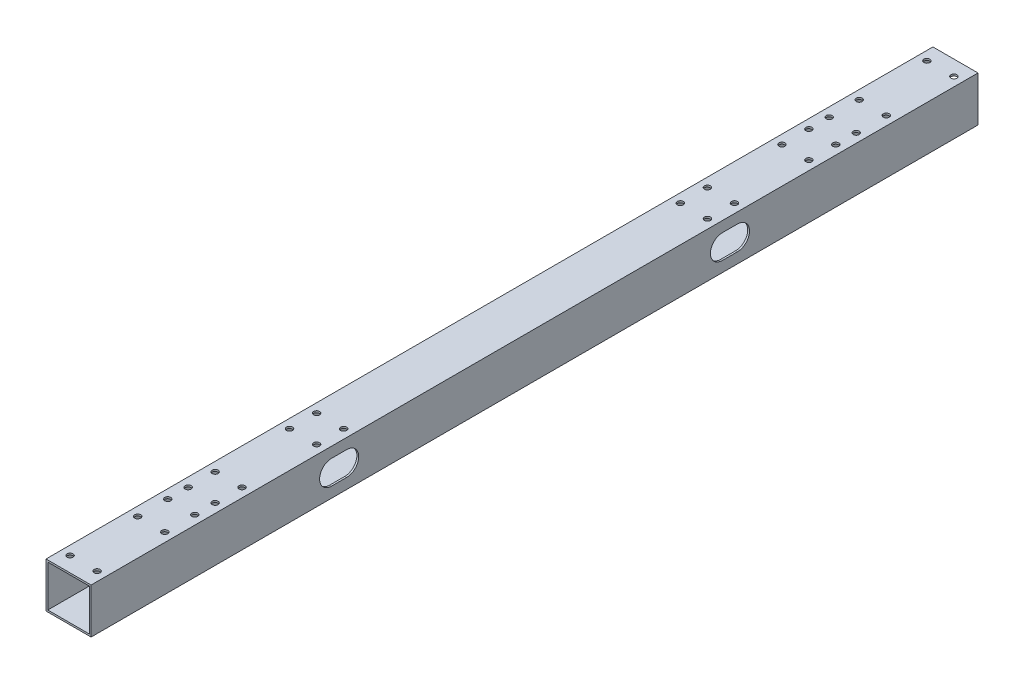
SolidWorks part; units mm, degrees
material "6063-T5"
ref_plane "前视基准面" through (0, 0, 0) normal (0, 0, 1) x (1, 0, 0)
ref_plane "上视基准面" through (0, 0, 0) normal (0, 1, 0) x (1, 0, 0)
ref_plane "右视基准面" through (0, 0, 0) normal (1, 0, 0) x (0, 0, -1)
sketch "草图1" plane through (0, 0, 0) normal (0, 0, 1) x (1, 0, 0)
  line L0 (-13.8, -13.8) -> (-13.8, 13.8)
  line L1 (-15, -15) -> (15, -15)
  line L2 (-15, -15) -> (-15, 15)
  line L3 (-15, 15) -> (15, 15)
  line L4 (15, -15) -> (15, 15)
  line L5 (0, 15) -> (0, -15) construction
  line L6 (-15, 0) -> (15, 0) construction
  line L7 (-13.8, 13.8) -> (13.8, 13.8)
  line L8 (13.8, -13.8) -> (13.8, 13.8)
  line L9 (-13.8, -13.8) -> (13.8, -13.8)
  point P0 (0, 0)
  dimension "D1" = 30
  dimension "D2" = 30
  dimension "D3" = 1.2
extrude "凸台-拉伸1" add sketch "草图1" along normal mid plane 590
sketch "草图2" plane through (0, 15, 0) normal (0, 1, 0) x (1, 0, 0)
  line L0 (0, 0) -> (15, 0) construction
  line L1 (15, -295) -> (15, 295) construction
  circle A0 centre (-9, 220) radius 2 construction
  circle A1 centre (9, 220) radius 2 construction
  circle A2 centre (-9, 240) radius 2 construction
  circle A3 centre (9, 240) radius 2 construction
  circle A4 centre (-9, 220) radius 2
  circle A5 centre (9, 220) radius 2
  circle A6 centre (-9, 240) radius 2
  circle A7 centre (9, 240) radius 2
  circle A8 centre (9, -240) radius 2
  circle A9 centre (-9, -240) radius 2
  circle A10 centre (9, -220) radius 2
  circle A11 centre (-9, -220) radius 2
extrude "切除-拉伸1" cut sketch "草图2" against normal blind 10
sketch "草图3" plane through (0, -13.8, 0) normal (0, 1, 0) x (1, 0, 0)
  line L0 (0, 0) -> (15, 0) construction
  line L1 (15, -295) -> (15, 295) construction
  circle A0 centre (-9, 240) radius 4
  circle A1 centre (9, 240) radius 4
  circle A2 centre (-9, 220) radius 4
  circle A3 centre (9, 220) radius 4
  circle A4 centre (9, -220) radius 4
  circle A5 centre (-9, -220) radius 4
  circle A6 centre (9, -240) radius 4
  circle A7 centre (-9, -240) radius 4
  dimension "D1" = 8
extrude "切除-拉伸2" cut sketch "草图3" against normal blind 10
sketch "草图4" plane through (15, 0, 0) normal (1, 0, 0) x (0, 0, -1)
  line L0 (-115, 15) -> (-145, 15) construction
  line L1 (-115, 15) -> (-145, 15) construction
  line L2 (-130, 15) -> (-130, -15) construction
  line L3 (-295, -15) -> (295, -15) construction
  line L4 (-135, 0) -> (-125, 0) construction
  line L5 (-135, 8) -> (-125, 8)
  line L6 (-135, -8) -> (-125, -8)
  arc A0 (-135, 8) -> (-135, -8) centre (-135, 0) ccw
  arc A1 (-125, -8) -> (-125, 8) centre (-125, 0) ccw
  point P8 (-130, 0)
  dimension "D2" = 8
  dimension "D1" = 10
extrude "切除-拉伸3" cut sketch "草图4" against normal blind 111
mirror "镜向1" about plane through (0, 0, 0) normal (0, 0, 1) of "切除-拉伸3"
sketch "草图5" plane through (0, 15, 0) normal (0, 1, 0) x (1, 0, 0)
  line L1 (-9, -139) -> (9, -139) construction
  line L2 (-9, -139) -> (-9, -121) construction
  line L3 (-9, -121) -> (9, -121) construction
  line L4 (9, -139) -> (9, -121) construction
  line L5 (0, -121) -> (0, -139) construction
  line L6 (-9, -130) -> (9, -130) construction
  circle A0 centre (-9, -139) radius 2 construction
  circle A1 centre (-9, -121) radius 2 construction
  circle A2 centre (9, -121) radius 2 construction
  circle A3 centre (-9, -139) radius 2
  circle A4 centre (-9, -121) radius 2
  circle A5 centre (9, -121) radius 2
  circle A6 centre (9, -139) radius 2
  point P9 (0, -130)
extrude "切除-拉伸4" cut sketch "草图5" against normal blind 10
mirror "镜向2" about plane through (0, 0, 0) normal (0, 0, 1) of "切除-拉伸4"
sketch "草图6" plane through (0, 15, 0) normal (0, 1, 0) x (1, 0, 0)
  line L0 (-9, -285) -> (9, -285) construction
  line L1 (15, -295) -> (-15, -295) construction
  line L2 (0, 0) -> (0, -285) construction
  circle A0 centre (-9, -285) radius 2
  circle A1 centre (9, -285) radius 2
  point P3 (0, -285)
  dimension "D3" = 4
  dimension "D1" = 10
  dimension "D2" = 18
extrude "切除-拉伸5" cut sketch "草图6" against normal blind 10
mirror "镜向3" about plane through (0, 0, 0) normal (0, 0, 1) of "切除-拉伸5"
sketch "草图7" plane through (0, -15, 0) normal (0, -1, 0) x (1, 0, 0)
  circle A0 centre (0, 98.7384) radius 1.5 construction
  circle A1 centre (0, 38.7384) radius 1.5 construction
  circle A2 centre (0, -38.7384) radius 1.5 construction
  circle A3 centre (0, -98.7384) radius 1.5 construction
  circle A4 centre (0, 98.7384) radius 1.5
  circle A5 centre (0, 38.7384) radius 1.5
  circle A6 centre (0, -38.7384) radius 1.5
  circle A7 centre (0, -98.7384) radius 1.5
extrude "切除-拉伸6" cut sketch "草图7" against normal blind 10
sketch "草图8" plane through (0, 13.8, 0) normal (0, -1, 0) x (1, 0, 0)
  circle A0 centre (-8.95, 188.55) radius 1.65 construction
  circle A1 centre (8.95, 188.55) radius 1.65 construction
  circle A2 centre (8.95, 206.45) radius 1.65 construction
  circle A3 centre (-8.95, 206.45) radius 1.65 construction
  circle A4 centre (-8.95, 188.55) radius 1.65 construction
  circle A5 centre (8.95, 188.55) radius 1.65 construction
  circle A6 centre (8.95, 206.45) radius 1.65 construction
  circle A7 centre (-8.95, 206.45) radius 1.65 construction
  circle A8 centre (8.95, 206.45) radius 2
  circle A9 centre (-8.95, 206.45) radius 2
  circle A10 centre (-8.95, 188.55) radius 2
  circle A11 centre (8.95, 188.55) radius 2
  dimension "D1" = 4
extrude "切除-拉伸7" cut sketch "草图8" against normal mid plane 92
mirror "镜向4" about plane through (0, 0, 0) normal (0, 0, 1) of "切除-拉伸7"
sketch "草图9" plane through (0, -15, 0) normal (0, -1, 0) x (1, 0, 0)
  line L0 (0, 0) -> (84.2196, 0) construction
  circle A0 centre (-8.95, 206.45) radius 4
  circle A1 centre (-9, 220) radius 4 construction
  circle A2 centre (8.95, 206.45) radius 4
  circle A3 centre (8.95, 188.55) radius 4
  circle A4 centre (-8.95, 188.55) radius 4
  circle A5 centre (-8.95, -188.55) radius 4
  circle A6 centre (8.95, -188.55) radius 4
  circle A7 centre (8.95, -206.45) radius 4
  circle A8 centre (-8.95, -206.45) radius 4
extrude "切除-拉伸8" cut sketch "草图9" against normal mid plane 10
